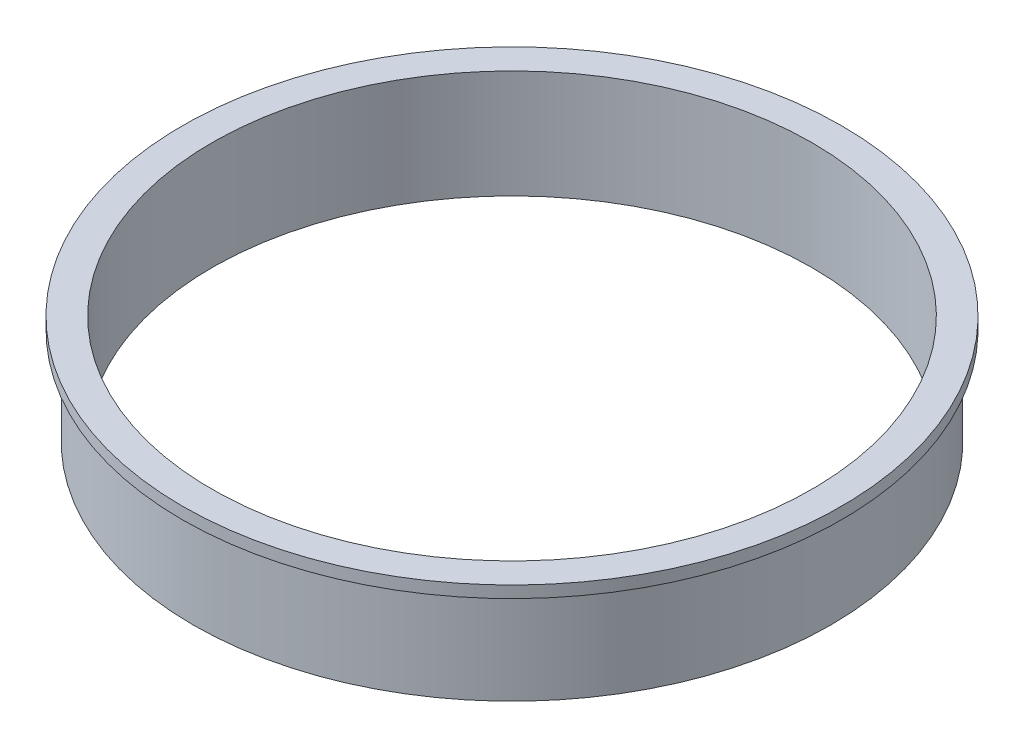
SolidWorks part; units mm, degrees
material "PLA/ABS"
ref_plane "Front Plane" through (0, 0, 0) normal (0, 0, 1) x (1, 0, 0)
ref_plane "Top Plane" through (0, 0, 0) normal (0, 1, 0) x (1, 0, 0)
ref_plane "Right Plane" through (0, 0, 0) normal (1, 0, 0) x (0, 0, -1)
other "Bounding Box"
ref_plane "Default Plane" through (-8.9266, -12.7485, 0) normal (-0.1736, 0.9848, 0) x (0.9848, 0.1736, 0)
sketch "Sketch2" plane through (0, 0, 0) normal (1, 0, 0) x (0, 0, -1)
  line L0 (0, 0) -> (0, 127994.1456) construction
  line L1 (-14.875, 0) -> (-14, 0)
  line L2 (-14, 0) -> (-14, 5.05)
  line L3 (-14, 5.05) -> (-15.375, 5.05)
  line L4 (-15.375, 5.05) -> (-15.375, 4.5)
  line L5 (-15.375, 4.5) -> (-14.875, 4.5)
  line L6 (-14.875, 4.5) -> (-14.875, 0)
  line L7 (-15, -6.6576) -> (-15, 49993.3424) construction
  line L8 (-13.9, -5.4452) -> (-13.9, 49994.5548) construction
  dimension "D1" = 0.1
  dimension "D2" = 0.875
  dimension "D3" = 0.55
  dimension "D4" = 4.5
  dimension "D5" = 0.5
  dimension "D6" = 15
  dimension "D7" = 13.9
revolve "Revolve1" add sketch "Sketch2" angle 360 about L0
